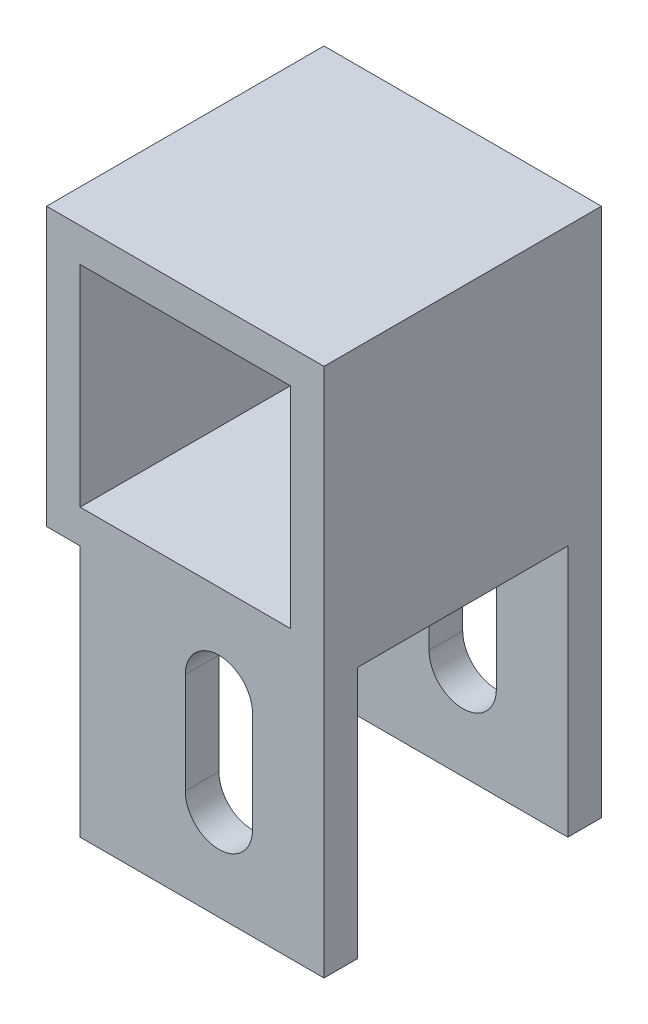
SolidWorks part; units mm, degrees
ref_plane "Front Plane" through (0, 0, 0) normal (0, 0, 1) x (1, 0, 0)
ref_plane "Top Plane" through (0, 0, 0) normal (0, 1, 0) x (1, 0, 0)
ref_plane "Right Plane" through (0, 0, 0) normal (1, 0, 0) x (0, 0, -1)
sketch "Sketch20" plane through (0, 0, 0) normal (0, 0, 1) x (1, 0, 0)
  line L1 (-16.5, 16.5) -> (16.5, 16.5)
  line L2 (-16.5, 16.5) -> (-16.5, -16.5)
  line L3 (-16.5, -16.5) -> (16.5, -16.5)
  line L4 (16.5, 16.5) -> (16.5, -16.5)
  line L5 (-16.5, 16.5) -> (16.5, -16.5) construction
  line L6 (-16.5, -16.5) -> (16.5, 16.5) construction
  line L7 (-12.5, 12.5) -> (12.5, 12.5)
  line L8 (-12.5, 12.5) -> (-12.5, -12.5)
  line L9 (-12.5, -12.5) -> (12.5, -12.5)
  line L10 (12.5, 12.5) -> (12.5, -12.5)
  line L11 (-12.381, 12.381) -> (12.381, -12.381) construction
  line L12 (-12.381, -12.381) -> (12.381, 12.381) construction
  line L13 (-12.5, 12.5) -> (12.5, -12.5) construction
  line L14 (-12.5, -12.5) -> (12.5, 12.5) construction
  point P0 (0, 0)
  point P6 (0, 0)
  point P11 (0, 0)
extrude "Boss-Extrude12" add sketch "Sketch20" along normal blind 33
sketch "Sketch22" plane through (0, -16.5, 0) normal (0, -1, 0) x (1, 0, 0)
  line L0 (16.5, 33) -> (16.5, 0) construction
  line L1 (-16.5, 33) -> (16.5, 33)
  line L2 (-16.5, 33) -> (-16.5, 29)
  line L3 (-16.5, 29) -> (16.5, 29)
  line L4 (16.5, 33) -> (16.5, 29)
  line L5 (-16.5, 33) -> (-16.5, 0) construction
  line L6 (16.5, 0) -> (-16.5, 0)
  line L7 (16.5, 0) -> (16.5, 4)
  line L8 (16.5, 4) -> (-16.5, 4)
  line L9 (-16.5, 0) -> (-16.5, 4)
extrude "Boss-Extrude13" add sketch "Sketch22" along normal blind 30 and the other way blind 4
sketch "Sketch23" plane through (0, -46.5, 0) normal (0, -1, 0) x (1, 0, 0)
  line L0 (16.5, 33) -> (-16.5, 33) construction
  line L1 (-16.5, 29) -> (-12.5, 29)
  line L2 (-16.5, 29) -> (-16.5, 33)
  line L3 (-16.5, 33) -> (-12.5, 33)
  line L4 (-12.5, 29) -> (-12.5, 33)
  line L5 (16.5, 4) -> (-16.5, 4) construction
  line L10 (-16.5, 0) -> (-12.5, 0)
  line L11 (-16.5, 0) -> (-16.5, 4)
  line L12 (-16.5, 4) -> (-12.5, 4)
  line L13 (-12.5, 0) -> (-12.5, 4)
extrude "Cut-Extrude10" cut sketch "Sketch23" against normal blind 30
sketch "Sketch36" plane through (0, 0, 0) normal (0, 0, -1) x (-1, 0, 0)
  line L0 (0, -12.5) -> (0, -23.5) construction
  line L1 (12.5, -12.5) -> (-12.5, -12.5) construction
  line L2 (12.5, -46.5) -> (-16.5, -46.5) construction
  line L3 (0, -12.5) -> (-4, -12.5) construction
  line L4 (-4, -12.5) -> (-4, -19.5) construction
  line L5 (-4, -12.5) -> (-8, -12.5) construction
  line L6 (-8, -12.5) -> (-8, -23.5) construction
  line L7 (0, -46.5) -> (0, -35.5) construction
  line L8 (-8, -46.5) -> (-8, -35.5) construction
  line L10 (-8, -23.5) -> (-8, -35.5)
  line L11 (0, -23.5) -> (0, -35.5)
  line L12 (-4, -39.5) -> (-4, -46.5) construction
  arc A0 (0, -23.5) -> (-8, -23.5) centre (-4, -23.5) ccw
  arc A1 (-8, -35.5) -> (0, -35.5) centre (-4, -35.5) ccw
extrude "Cut-Extrude15" cut sketch "Sketch36" against normal blind 33
